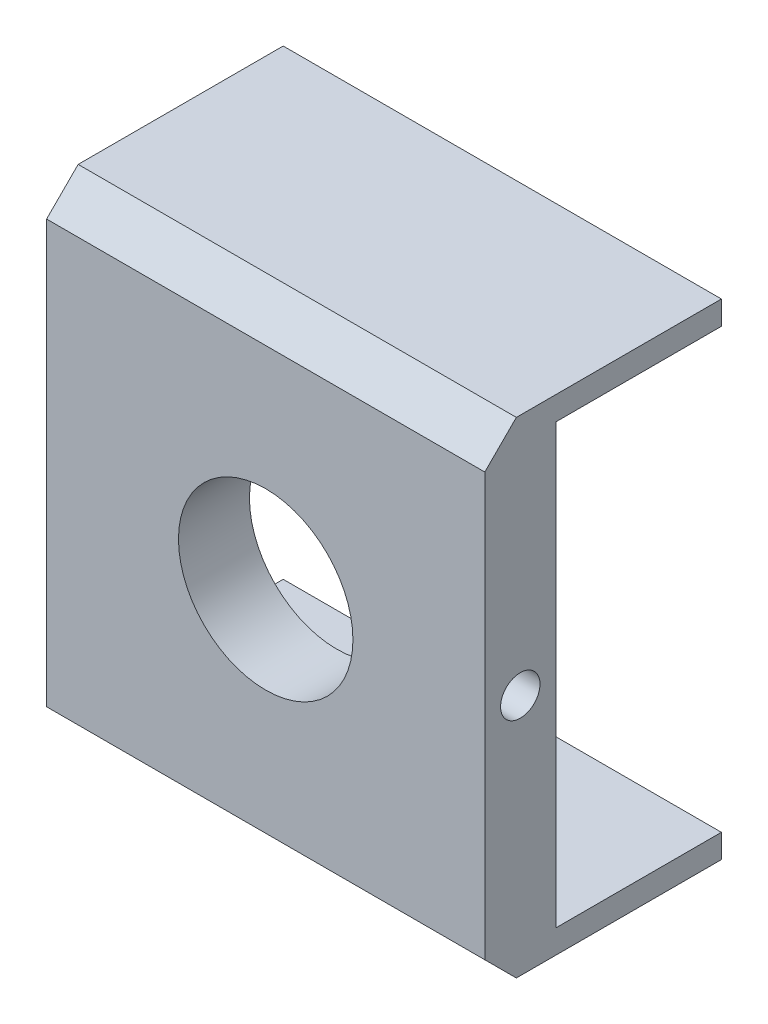
SolidWorks part; units mm, degrees
material "6061-T6 (SS)"
ref_plane "Front Plane" through (0, 0, 0) normal (0, 0, 1) x (1, 0, 0)
ref_plane "Top Plane" through (0, 0, 0) normal (0, 1, 0) x (1, 0, 0)
ref_plane "Right Plane" through (0, 0, 0) normal (1, 0, 0) x (0, 0, -1)
sketch "Sketch1" plane through (0, 0, 0) normal (0, 0, 1) x (1, 0, 0)
  line L1 (-17.6403, -19.5453) -> (17.6403, -19.5453)
  line L2 (-17.6403, -19.5453) -> (-17.6403, 19.5453)
  line L3 (-17.6403, 19.5453) -> (17.6403, 19.5453)
  line L4 (17.6403, -19.5453) -> (17.6403, 19.5453)
  line L5 (-17.6403, -19.5453) -> (17.6403, 19.5453) construction
  line L6 (-17.6403, 19.5453) -> (17.6403, -19.5453) construction
  point P0 (0, 0)
  dimension "D1" = 35.2806
  dimension "D2" = 39.0906
extrude "Extrude1" add sketch "Sketch1" along normal mid plane 19.05
sketch "Sketch2" plane through (0, 0, 9.525) normal (0, 0, 1) x (1, 0, 0)
  circle A0 centre (0, 0) radius 7.0231
  dimension "D1" = 14.0462
extrude "Extrude2" cut sketch "Sketch2" against normal through all
sketch "Sketch3" plane through (-17.6403, 0, 0) normal (-1, 0, 0) x (0, 0, 1)
  line L0 (-9.525, 17.6403) -> (3.81, 17.6403)
  line L1 (-9.525, 19.5453) -> (-9.525, -19.5453) construction
  line L2 (3.81, 17.6403) -> (3.81, -17.6403)
  line L3 (3.81, -17.6403) -> (-9.525, -17.6403)
  line L4 (-9.525, -17.6403) -> (-9.525, 0)
  line L5 (-9.525, 0) -> (-9.525, 17.6403)
  dimension "D1" = 35.2806
  dimension "D2" = 13.335
extrude "Extrude4" cut sketch "Sketch3" against normal through all
sketch "Sketch4" plane through (-17.6403, 0, 0) normal (-1, 0, 0) x (0, 0, 1)
  line L0 (9.525, 0) -> (3.81, 0) construction
  line L1 (9.525, 19.5453) -> (9.525, -19.5453) construction
  line L2 (3.81, -17.6403) -> (3.81, 17.6403) construction
  point P6 (6.6675, 0)
hole_wizard "1/8 (0.125) Diameter Hole1" positions "3DSketch1" profile "Sketch5" hole size "1/8" standard "Ansi Inch"
sketch3d "3DSketch1"
  point P0 (-17.6403, 0, 6.6675)
sketch "Sketch5" plane through (-17.6403, 0, 6.6675) normal (0, 1, 0) x (0, 0, 1)
  line L0 (0, 0) -> (0, 7.3039)
  line L1 (0, 7.3039) -> (1.5875, 6.35)
  line L2 (1.5875, 6.35) -> (1.5875, 0)
  line L5 (1.5875, 0) -> (0, 0)
  line L10 (0, 7.3039) -> (-1.5875, 6.35) construction
  line L11 (0, -6.35) -> (0, 107.95) construction
  dimension "Hole Dia." = 3.175
  dimension "Hole Depth" = 6.35
  dimension "Drill Angle" = 118
mirror "Mirror1" about plane through (0, 0, 0) normal (1, 0, 0) of "1/8 (0.125) Diameter Hole1"
chamfer "Chamfer1" distance 2.54 angle 45 2 edges at (0, -19.5453, 9.525) (0, 19.5453, 9.525)
